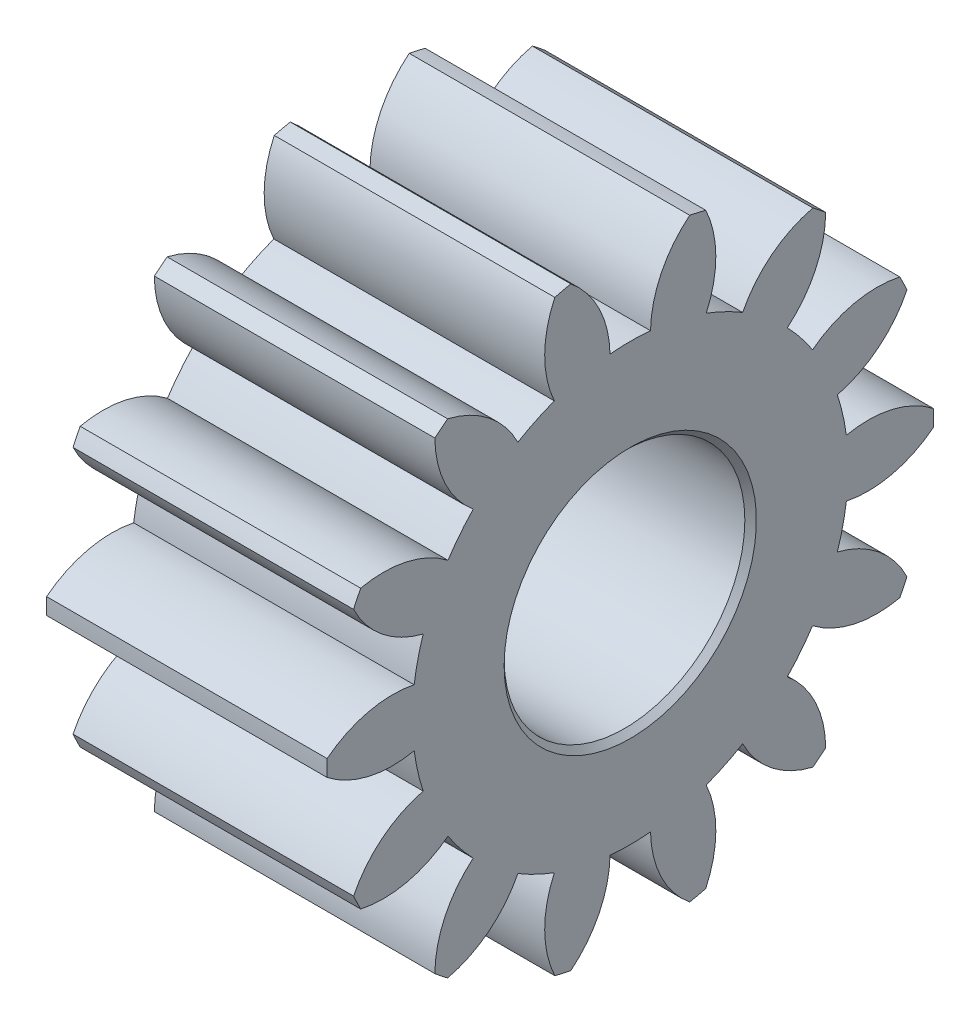
SolidWorks part; units mm, degrees
ref_plane "Plane1" through (0, 0, 0) normal (0, 0, 1) x (1, 0, 0)
ref_plane "Plane2" through (0, 0, 0) normal (0, 1, 0) x (1, 0, 0)
ref_plane "Plane3" through (0, 0, 0) normal (1, 0, 0) x (0, 0, -1)
sketch "HoldingSke" plane through (0, 0, 0) normal (0, 1, 0) x (1, 0, 0)
  line L0 (0, 0) -> (19.4059, -4.8384)
  line L1 (-15, 0) -> (100, 0) construction
  line L2 (0, 0) -> (-2.1039, 2.3779)
  line L3 (0, 0) -> (-11.863, 4.5341)
  line L4 (0, 0) -> (8.3795, 2.0892)
  line L5 (0, 0) -> (-46.8476, -17.4728)
  line L6 (0, 0) -> (-30.6716, -20.6942)
  line L7 (-2.1039, 2.3779) -> (8.6587, 51.2063)
  line L8 (-76.2, 54.61) -> (-72.9, 54.61)
  line L9 (-71.009, 38.7566) -> (-53.1078, 45.2721)
  line L10 (-76.2, 71.12) -> (104.1128, 71.12)
  line L11 (0, 0) -> (-37, 0)
  line L12 (-76.2, 101.6) -> (-76.033, 101.6)
  line L13 (24.9733, 27.94) -> (52.9518, 28.4284)
  line L14 (24.9733, 27.94) -> (24.9743, 27.94)
  line L15 (24.9733, 27.94) -> (100.4006, 29.5858)
  line L16 (-63.627, -5) -> (-12.827, -5)
  circle A0 centre (0, 0) radius 16
  circle A1 centre (0, 0) radius 28.749
  circle A2 centre (0, 0) radius 37.5
  circle A3 centre (0, 0) radius 16
  dimension "MHD" = 57.498
  dimension "Hub_dia" = 75
  dimension "Bore" = 32
  dimension "MBD" = 32
  dimension "Num_teeth" = 14
  dimension "Overall_len" = 50
  dimension "Show_teeth" = 14
  dimension "Thickness" = 37
  dimension "OAL" = 50.0005
  dimension "T_dim" = 3.3
  dimension "Ap" = 20
  dimension "H" = 19.05
  dimension "Pitch_radius" = 180.3128
  dimension "Width" = 37
  dimension "Backlash" = 0.167
  dimension "Addendum_fac" = 1
  dimension "Dedendum_fac" = 1.25
  dimension "Clearance_fac" = 0.25
  dimension "Dedendum_add" = 0.001
  dimension "Module" = 5
sketch "BasProSke" plane through (0, 0, 0) normal (0, 1, 0) x (1, 0, 0)
  line L0 (-10, 0) -> (60, 0) construction
  line L1 (0, 0) -> (0, 40)
  line L2 (0, 0) -> (37, 0)
  line L3 (37, 0) -> (37, 40)
  line L4 (37, 40) -> (0, 40)
  dimension "Thickness" = 37
  dimension "Diameter" = 80
revolve "Base-Revolve" add sketch "BasProSke" angle 360 about L0
sketch "TooCutSke" plane through (0, 0, 0) normal (1, 0, 0) x (0, 0, -1)
  line L1 (0, 0) -> (0, 107) construction
  line L2 (0, 0) -> (-4.2107, 34.7458) construction
  line L3 (0, 0) -> (-15.4926, 67.8776) construction
  line L4 (-4.2107, 34.7458) -> (-7.7463, 33.9388) construction
  arc A0 (2.669, 28.6248) -> (-2.669, 28.6248) centre (0, 0) ccw
  arc A1 (8.1036, 39.4299) -> (-8.1036, 39.4299) centre (0, 0) ccw
  circle A2 centre (0, 0) radius 35 construction
  circle A3 centre (0, 0) radius 32.8892 construction
  arc A4 (-2.669, 28.6248) -> (-8.1036, 39.4299) centre (-16.6663, 28.3538) ccw
  arc A5 (8.1036, 39.4299) -> (2.669, 28.6248) centre (16.6663, 28.3538) ccw
  dimension "Root_dia" = 57.498
  dimension "Pitch_dia" = 70
  dimension "Base_dia" = 65.7785
  dimension "Flank_rad" = 14
  dimension "Half_ang" = 12.857
  dimension "Half_CT" = 3.6265
extrude "ToothCut" cut sketch "TooCutSke" along normal through all
fillet "Breaks" [suppressed] radius 0.1
fillet "RootFillets" [suppressed] radius 1.251
pattern_circular "TeethCuts" count 14 every 25.714 about axis through (-10, 0, 0) along (1, 0, 0) of "ToothCut", "RootFillets", "Breaks"
sketch "HubNeaOneSke" plane through (0, 0, 0) normal (-1, 0, 0) x (0, 0, 1)
  circle A0 centre (0, 0) radius 28.749
  dimension "Diameter" = 57.498
extrude "HubNearOne" [suppressed] add sketch "HubNeaOneSke" along normal blind 13.0005
sketch "HubNeaBotSke" plane through (0, 0, 0) normal (-1, 0, 0) x (0, 0, 1)
  circle A0 centre (0, 0) radius 28.749
  dimension "Diameter" = 57.498
extrude "HubNearBoth" [suppressed] add sketch "HubNeaBotSke" along normal blind 6.5003
ref_plane "FarPln" through (37, 0, 0) normal (1, 0, 0) x (0, 0, -1)
sketch "HubFarSke" plane through (37, 0, 0) normal (1, 0, 0) x (0, 0, -1)
  circle A0 centre (0, 0) radius 28.749
  dimension "Diameter" = 57.498
extrude "HubFar" [suppressed] add sketch "HubFarSke" along normal blind 6.5003
sketch "BorSke" plane through (0, 0, 0) normal (1, 0, 0) x (0, 0, -1)
  circle A0 centre (0, 0) radius 15.875
  dimension "D1" = 31.75
extrude "Bore" cut sketch "BorSke" along normal mid plane 100.001
sketch "KeySke" plane through (0, 0, 0) normal (1, 0, 0) x (0, 0, -1)
  line L0 (-5, 0) -> (-5, 19.3)
  line L1 (-5, 19.3) -> (5, 19.3)
  line L2 (5, 19.3) -> (5, 0)
  line L3 (0, 0) -> (0, 34) construction
  line L4 (-5, 0) -> (5, 0)
  dimension "Offset" = 19.3
  dimension "Width" = 10
extrude "Keyway" [suppressed] cut sketch "KeySke" along normal mid plane 100.001
pattern_circular "Keyway2" [suppressed] count 2 every 90 about axis through (-10, 0, 0) along (1, 0, 0)
chamfer "Chamfer1" distance 0.762 angle 45 2 edges at (37, 0, 15.875) (0, 0, -15.875)
equation "' \"Module@HoldingSke\" = 6.35"
equation "' \"Num_teeth@HoldingSke\" = 12"
equation "' \"Ap@HoldingSke\" =  20"
equation "' \"Ap@HoldingSke\" = 20"
equation "' \"Width@HoldingSke\" = 0.5 * 25.4"
equation "' \"Hub_dia@HoldingSke\"= 1 * 25.4"
equation "' \"Hub_dia@HoldingSke\" = 1 * 25.4"
equation "' \"Overall_len@HoldingSke\" = 1.0 * 25.4"
equation "' \"Bore@HoldingSke\" = 0.75 * 25.4"
equation "' \"T_dim@HoldingSke\" = 0.1 * 25.4"
equation "' \"Width@KeySke\" = 0.25 * 25.4"
equation "' \"Show_teeth@HoldingSke\" = 13"
equation "' \"Backlash@HoldingSke\" = 0.009 * 25.4"
equation "' \"Addendum_fac@HoldingSke\" = 1.0"
equation "' \"Dedendum_fac@HoldingSke\" = 1.25"
equation "' \"Dedendum_add@HoldingSke\" = 0.00005 * 25.4"
equation "' \"Clearance_fac@HoldingSke\" = 0.25"
equation "\"Pitch@HoldingSke\" = 1 / \"Module@HoldingSke\""
equation "\"Overcut_dia@TooCutSke\" = (\"Num_teeth@HoldingSke\" + 2 * \"Addendum_fac@HoldingSke\") / \"Pitch@HoldingSke\" + 0.002 * 25.4"
equation "\"Pitch_dia@TooCutSke\" = \"Num_teeth@HoldingSke\" / \"Pitch@HoldingSke\""
equation "\"Base_dia@TooCutSke\" = \"Num_teeth@HoldingSke\" / \"Pitch@HoldingSke\" * cos((\"Ap@HoldingSke\"  * 3.14159265 / 180))"
equation "\"Root_dia@TooCutSke\" = (\"Num_teeth@HoldingSke\" + 2) / \"Pitch@HoldingSke\" - 2 * (\"Addendum_fac@HoldingSke\" + \"Dedendum_fac@HoldingSke\") / \"Pitch@HoldingSke\" - \"Dedendum_add@HoldingSke\" * 2"
equation "\"Half_ang@TooCutSke\" = 180 / \"Num_teeth@HoldingSke\""
equation "\"Half_CT@TooCutSke\" = \"Num_teeth@HoldingSke\" / \"Pitch@HoldingSke\" * sin((3.14159265 / 2 / \"Num_teeth@HoldingSke\")) / 2 - 7 * \"Backlash@HoldingSke\" / 4"
equation "\"Flank_rad@TooCutSke\" = \"Num_teeth@HoldingSke\" / \"Pitch@HoldingSke\" / 5"
equation "\"Radius@RootFillets\" = \"Clearance_fac@HoldingSke\" / \"Pitch@HoldingSke\" + \"Dedendum_add@HoldingSke\""
equation "\"Break_rad@Breaks\" = 0.02 / \"Pitch@HoldingSke\""
equation "\"Thickness@HoldingSke\" = \"Width@HoldingSke\""
equation "\"OAL@HoldingSke\" = \"Thickness@HoldingSke\""
equation "\"MHD@HoldingSke\" = (\"Num_teeth@HoldingSke\" + 2) / \"Pitch@HoldingSke\" - 2 * (\"Addendum_fac@HoldingSke\" + \"Dedendum_fac@HoldingSke\")  / \"Pitch@HoldingSke\" - \"Dedendum_add@HoldingSke\" * 2"
equation "\"MBD@HoldingSke\" = (\"Num_teeth@HoldingSke\" + 2) / \"Pitch@HoldingSke\" - 2 * (\"Addendum_fac@HoldingSke\" + \"Dedendum_fac@HoldingSke\")  / \"Pitch@HoldingSke\" - \"Dedendum_add@HoldingSke\" * 2 - 0.002 * 25.4"
equation "\"MHD@HoldingSke\" = ((sgn( \"MHD@HoldingSke\" - \"Hub_dia@HoldingSke\" )-1)*( \"MHD@HoldingSke\" - \"Hub_dia@HoldingSke\" ))/-2+ \"Hub_dia@HoldingSke\""
equation "\"MBD@HoldingSke\" = ((sgn( \"MBD@HoldingSke\" - \"Bore@HoldingSke\" )-1)*( \"MBD@HoldingSke\" - \"Bore@HoldingSke\" ))/-2+ \"Bore@HoldingSke\""
equation "\"OAL@HoldingSke\" = ((sgn( \"OAL@HoldingSke\" - \"Overall_len@HoldingSke\" )+1)*( \"OAL@HoldingSke\" - \"Overall_len@HoldingSke\" ))/2 + \"Overall_len@HoldingSke\" + 0.000002 * 25.4"
equation "\"Num_teeth@TeethCuts\" = int( \"Show_teeth@HoldingSke\" ) + 1"
equation "\"Num_teeth@TeethCuts\" = ((sgn( \"Num_teeth@TeethCuts\" - \"Num_teeth@HoldingSke\" )-1)*( \"Num_teeth@TeethCuts\" - \"Num_teeth@HoldingSke\" ))/-2+ \"Num_teeth@HoldingSke\""
equation "\"Num_teeth@TeethCuts\" = ((sgn( \"Num_teeth@TeethCuts\" - 2.0)+1)*( \"Num_teeth@TeethCuts\" - 2.0))/2 +2.0"
equation "\"Angle@TeethCuts\" = 360.0 / \"Num_teeth@HoldingSke\""
equation "\"Diameter@BasProSke\" = (\"Num_teeth@HoldingSke\" + 2 * \"Addendum_fac@HoldingSke\") / \"Pitch@HoldingSke\""
equation "\"Thickness@BasProSke\"  = \"Thickness@HoldingSke\""
equation "' \"Fillet_rad@BasProSke\" =  \"Thickness@HoldingSke\" * 0.05"
equation "' \"Fillet_rad@BasProSke\" = \"Thickness@HoldingSke\" * 0.05"
equation "\"MHD@HoldingSke\" = ((sgn( \"MHD@HoldingSke\" - \"Root_dia@TooCutSke\" )-1)*( \"MHD@HoldingSke\" - \"Root_dia@TooCutSke\" ))/-2+ \"Root_dia@TooCutSke\""
equation "\"Diameter@HubNeaOneSke\" = \"MHD@HoldingSke\""
equation "\"Length@HubNearOne\" = \"OAL@HoldingSke\" - \"Thickness@BasProSke\""
equation "\"Diameter@HubNeaBotSke\" = \"MHD@HoldingSke\""
equation "\"Length@HubNearBoth\" = ( \"OAL@HoldingSke\" - \"Thickness@BasProSke\" ) / 2.0"
equation "\"Thickness@FarPln\" = \"Thickness@BasProSke\""
equation "\"Diameter@HubFarSke\" = \"MHD@HoldingSke\""
equation "\"Length@HubFar\" = ( \"OAL@HoldingSke\" - \"Thickness@BasProSke\" ) / 2.0"
equation "\"D1@Bore\" = \"OAL@HoldingSke\" * 2.0"
equation "\"D1@Keyway\" = \"OAL@HoldingSke\" * 2.0"
equation "\"Offset@KeySke\" = \"T_dim@HoldingSke\" + \"MBD@HoldingSke\" / 2.0"
